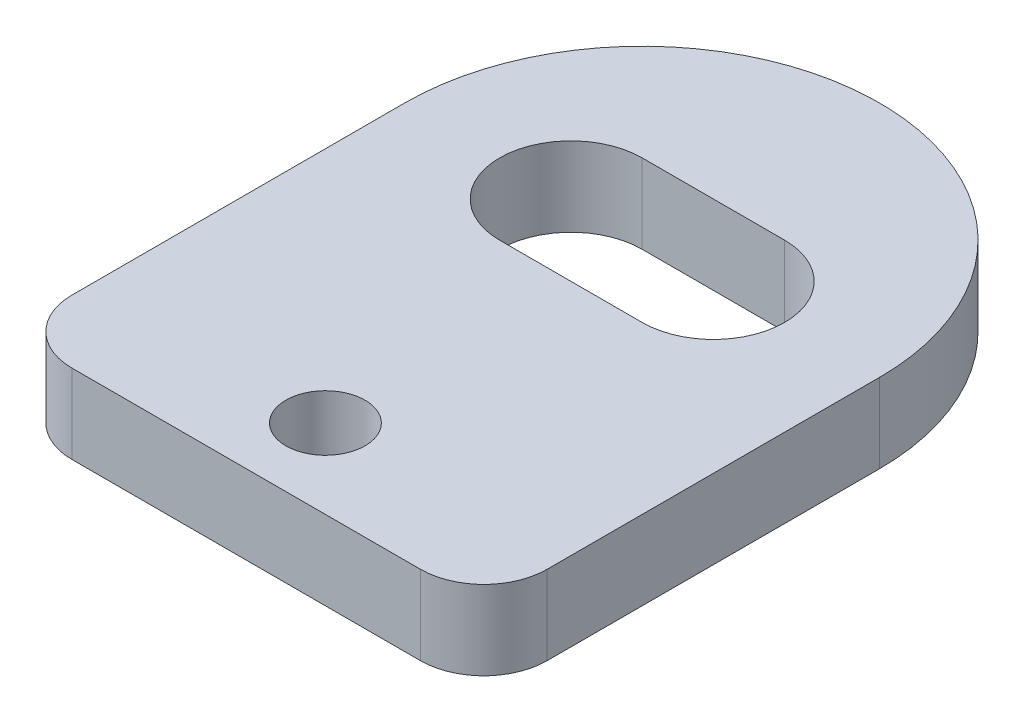
SolidWorks part; units mm, degrees
ref_plane "Front Plane" through (0, 0, 0) normal (0, 0, 1) x (1, 0, 0)
ref_plane "Top Plane" through (0, 0, 0) normal (0, 1, 0) x (1, 0, 0)
ref_plane "Right Plane" through (0, 0, 0) normal (1, 0, 0) x (0, 0, -1)
sketch "Sketch2" plane through (0, 0, 0) normal (0, 1, 0) x (1, 0, 0)
  line L0 (0, 25.4) -> (0, -25.4) construction
  line L1 (-19.05, -25.4) -> (19.05, -25.4)
  line L2 (-19.05, -25.4) -> (-19.05, 25.4)
  line L3 (-19.05, 25.4) -> (19.05, 25.4)
  line L4 (19.05, -25.4) -> (19.05, 25.4)
  line L5 (-19.05, -25.4) -> (19.05, 25.4) construction
  line L6 (-19.05, 25.4) -> (19.05, -25.4) construction
  line L7 (-19.05, 6.35) -> (19.05, 6.35) construction
  line L8 (-5.715, 6.35) -> (5.715, 6.35) construction
  line L9 (-5.715, 12.065) -> (5.715, 12.065)
  line L10 (-5.715, 0.635) -> (5.715, 0.635)
  line L11 (0, -25.4) -> (0, -19.05) construction
  arc A0 (19.05, 6.35) -> (-19.05, 6.35) centre (0, 6.35) ccw
  arc A1 (-5.715, 12.065) -> (-5.715, 0.635) centre (-5.715, 6.35) ccw
  arc A2 (5.715, 0.635) -> (5.715, 12.065) centre (5.715, 6.35) ccw
  circle A3 centre (0, -19.05) radius 3.175
  point P0 (0, 0)
  point P13 (0, 6.35)
  point P18 (-11.43, 6.35)
  point P19 (11.43, 6.35)
  dimension "D3" = 22.86
  dimension "D6" = 6.35
  dimension "D1" = 50.8
  dimension "D2" = 38.1
  dimension "D4" = 11.43
  dimension "D5" = 6.35
extrude "Boss-Extrude1" add sketch "Sketch2" along normal mid plane 6.35 contours L4 A0 L2 L1 A3 A2 L10 A1 L9
fillet "Fillet1" radius 5.08 2 edges at (19.05, 0, 25.4) (-19.05, 0, 25.4)
